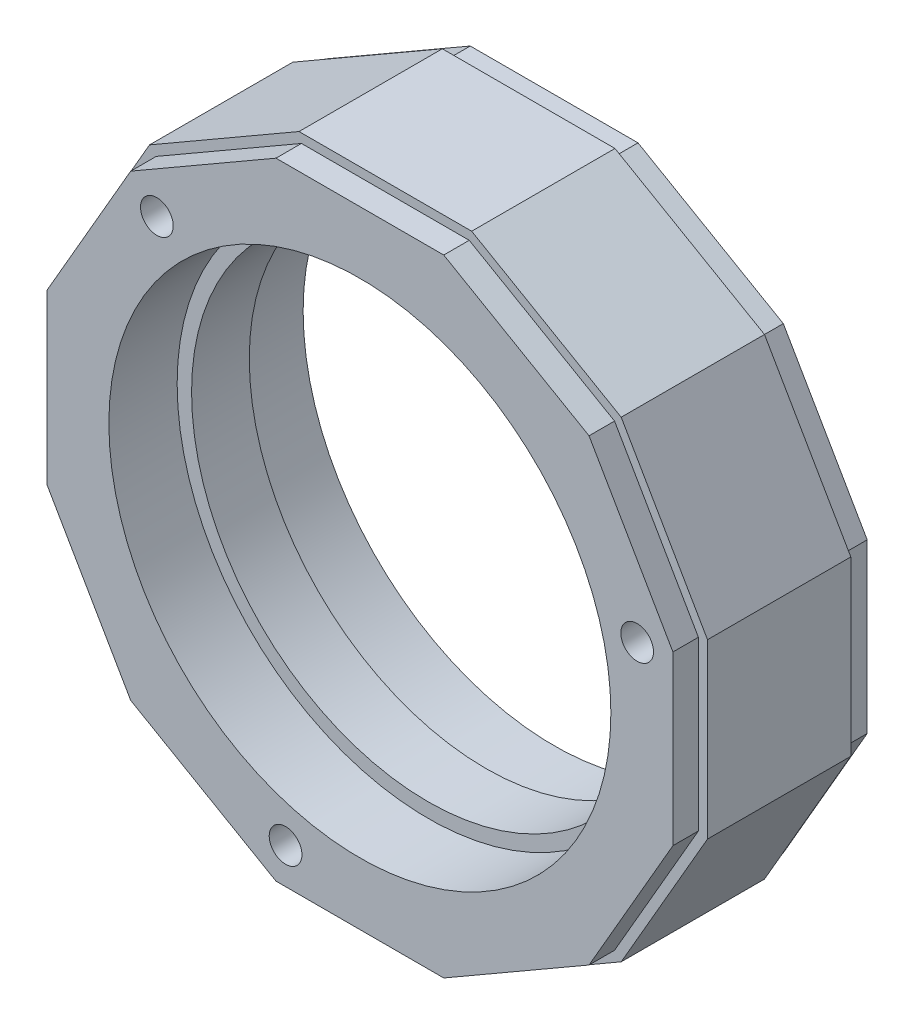
SolidWorks part; units mm, degrees
ref_plane "Front Plane" through (0, 0, 0) normal (0, 0, 1) x (1, 0, 0)
ref_plane "Top Plane" through (0, 0, 0) normal (0, 1, 0) x (1, 0, 0)
ref_plane "Right Plane" through (0, 0, 0) normal (1, 0, 0) x (0, 0, -1)
sketch "S01 - Smaller twelve-flat end bead seats" plane through (0, 0, 0) normal (0, 0, 1) x (1, 0, 0)
  line L0 (32.5517, 8.7222) -> (23.8295, 23.8295)
  line L1 (23.8295, 23.8295) -> (8.7222, 32.5517)
  line L2 (8.7222, 32.5517) -> (-8.7222, 32.5517)
  line L3 (-8.7222, 32.5517) -> (-23.8295, 23.8295)
  line L4 (-23.8295, 23.8295) -> (-32.5517, 8.7222)
  line L5 (-32.5517, 8.7222) -> (-32.5517, -8.7222)
  line L6 (-32.5517, -8.7222) -> (-23.8295, -23.8295)
  line L7 (-23.8295, -23.8295) -> (-8.7222, -32.5517)
  line L8 (-8.7222, -32.5517) -> (8.7222, -32.5517)
  line L9 (8.7222, -32.5517) -> (23.8295, -23.8295)
  line L10 (23.8295, -23.8295) -> (32.5517, -8.7222)
  line L11 (32.5517, -8.7222) -> (32.5517, 8.7222)
  circle A0 centre (0, 0) radius 24.6
  dimension "D1" = 49.2
  dimension "D2" = 8.7222
  dimension "D3" = 23.8295
  dimension "D4" = 32.5517
  dimension "D5" = 8.7222
  dimension "D6" = 23.8295
  dimension "D7" = 32.5517
  dimension "D8" = 8.7222
  dimension "D9" = 23.8295
  dimension "D10" = 32.5517
  dimension "D11" = 8.7222
  dimension "D12" = 23.8295
  dimension "D13" = 32.5517
extrude "01 - Smaller twelve-flat end bead seats" add sketch "S01 - Smaller twelve-flat end bead seats" along normal blind 20.2
sketch "S02 - Raised central tyre drive key" plane through (0, 0, 0) normal (0, 0, 1) x (1, 0, 0)
  line L0 (33.4983, 8.9758) -> (24.5225, 24.5225)
  line L1 (24.5225, 24.5225) -> (8.9758, 33.4983)
  line L2 (8.9758, 33.4983) -> (-8.9758, 33.4983)
  line L3 (-8.9758, 33.4983) -> (-24.5225, 24.5225)
  line L4 (-24.5225, 24.5225) -> (-33.4983, 8.9758)
  line L5 (-33.4983, 8.9758) -> (-33.4983, -8.9758)
  line L6 (-33.4983, -8.9758) -> (-24.5225, -24.5225)
  line L7 (-24.5225, -24.5225) -> (-8.9758, -33.4983)
  line L8 (-8.9758, -33.4983) -> (8.9758, -33.4983)
  line L9 (8.9758, -33.4983) -> (24.5225, -24.5225)
  line L10 (24.5225, -24.5225) -> (33.4983, -8.9758)
  line L11 (33.4983, -8.9758) -> (33.4983, 8.9758)
  circle A0 centre (0, 0) radius 24.6
  dimension "D1" = 49.2
  dimension "D2" = 8.9758
  dimension "D3" = 24.5225
  dimension "D4" = 33.4983
  dimension "D5" = 8.9758
  dimension "D6" = 24.5225
  dimension "D7" = 33.4983
  dimension "D8" = 8.9758
  dimension "D9" = 24.5225
  dimension "D10" = 33.4983
  dimension "D11" = 8.9758
  dimension "D12" = 24.5225
  dimension "D13" = 33.4983
extrude "02 - Raised central tyre drive key" add sketch "S02 - Raised central tyre drive key" along normal blind 14.9 from offset 2.65
sketch "S03 - Inboard 6808 outer race seat" plane through (0, 0, 0) normal (0, 0, 1) x (1, 0, 0)
  circle A0 centre (0, 0) radius 26.1
  dimension "D1" = 52.2
extrude "03 - Inboard 6808 outer race seat" cut sketch "S03 - Inboard 6808 outer race seat" along normal blind 7.2 from offset 0.1 offset against normal yes
sketch "S04 - Outboard 6808 outer race seat" plane through (0, 0, 0) normal (0, 0, 1) x (1, 0, 0)
  circle A0 centre (0, 0) radius 26.1
  dimension "D1" = 52.2
extrude "04 - Outboard 6808 outer race seat" cut sketch "S04 - Outboard 6808 outer race seat" along normal blind 7.2 from offset 13.1
sketch "S05 - Three tyre-flange through holes" plane through (0, 0, 0) normal (0, 0, 1) x (1, 0, 0)
  circle A0 centre (28.8329, 7.7257) radius 1.7
  circle A1 centre (-21.1071, 21.1071) radius 1.7
  circle A2 centre (-7.7257, -28.8329) radius 1.7
  dimension "D1" = 3.4
  dimension "D2" = 3.4
  dimension "D3" = 3.4
  dimension "D4" = 28.8329
  dimension "D5" = 7.7257
  dimension "D6" = 21.1071
  dimension "D7" = 7.7257
  dimension "D8" = 21.1071
  dimension "D9" = 28.8329
extrude "05 - Three tyre-flange through holes" cut sketch "S05 - Three tyre-flange through holes" along normal blind 20.4 from offset 0.1
